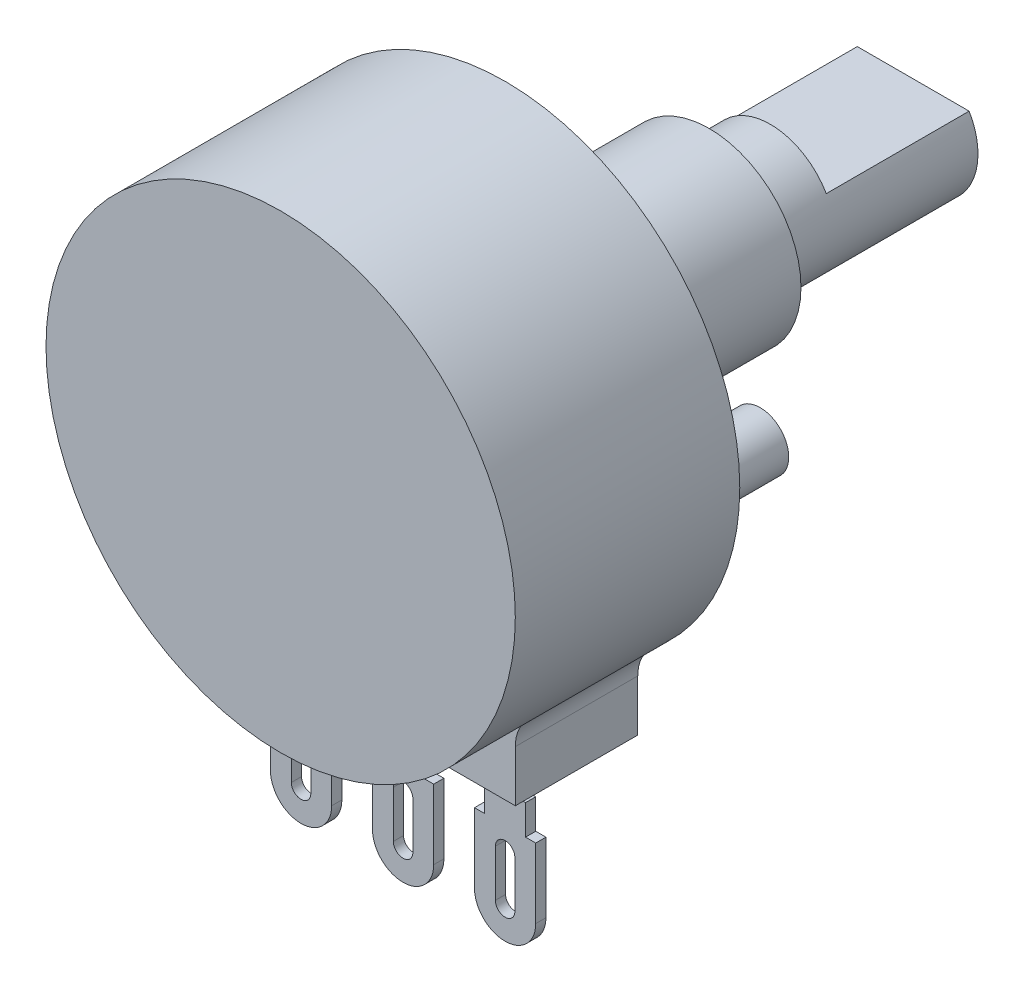
SolidWorks part; units mm, degrees
ref_plane "Front Plane" through (0, 0, 0) normal (0, 0, 1) x (1, 0, 0)
ref_plane "Top Plane" through (0, 0, 0) normal (0, 1, 0) x (1, 0, 0)
ref_plane "Right Plane" through (0, 0, 0) normal (1, 0, 0) x (0, 0, -1)
sketch "Sketch1" plane through (0, 0, 0) normal (1, 0, 0) x (0, 0, -1)
  line L0 (-360.0551, 0) -> (17642.7019, 0) construction
  line L1 (0, -360.0551) -> (0, 17642.7019) construction
  line L2 (0, 0) -> (0, 11.5)
  line L3 (0, 11.5) -> (11, 11.5)
  line L4 (11, 11.5) -> (11, 4.5)
  line L5 (11, 4.5) -> (21, 4.5)
  line L6 (21, 4.5) -> (21, 3.175)
  line L7 (21, 3.175) -> (31, 3.175)
  line L8 (31, 3.175) -> (31, 0)
  line L9 (0, 0) -> (31, 0)
  dimension "D1" = 23
  dimension "D2" = 11
  dimension "D3" = 10
  dimension "D4" = 20
  dimension "D5" = 9
  dimension "D6" = 6.35
revolve "Revolve1" add sketch "Sketch1" angle 360 about L9
sketch "Sketch2" plane through (0, 0, -11) normal (0, 0, -1) x (-1, 0, 0)
  circle A0 centre (-10, 0) radius 1.4
  dimension "D1" = 2.8
  dimension "D2" = 10
extrude "Boss-Extrude1" add sketch "Sketch2" along normal blind 2.5
ref_plane "Plane1" through (0, 0, -5) normal (0, 0, -1) x (-1, 0, 0)
sketch "Sketch3" plane through (0, 0, -5) normal (0, 0, -1) x (-1, 0, 0)
  line L0 (-1000, 0) -> (49000, 0) construction
  line L5 (0, -1000) -> (0, 49000) construction
  line L7 (-6.5, -8.3134) -> (6.5, -8.3134)
  line L8 (-6.5, -8.3134) -> (-6.5, -13)
  line L9 (-6.5, -13) -> (6.5, -13)
  line L10 (6.5, -8.3134) -> (6.5, -13)
  line L11 (-6.5, -8.3134) -> (6.5, -13) construction
  line L12 (-6.5, -13) -> (6.5, -8.3134) construction
  point P1 (0, -10.6567)
  dimension "D1" = 13
  dimension "D2" = 13
extrude "Boss-Extrude3" add sketch "Sketch3" along normal up to surface (6 mm away) up to face at (11.4, 0, -11)
fillet "Fillet1" radius 2 2 edges at (-6.5, -9.4868, -8) (6.5, -9.4868, -8)
ref_plane "Plane2" through (0, 0, -6) normal (0, 0, -1) x (-1, 0, 0)
sketch "Sketch4" plane through (0, 0, -6) normal (0, 0, -1) x (-1, 0, 0)
  line L0 (-5.4205, -13) -> (-5.4205, -13.6163)
  line L1 (-1.5, -18.5) -> (-1.5, -15.0805)
  line L2 (6.5, -13) -> (-6.5, -13) construction
  line L3 (-5.4205, -13.6163) -> (-6, -13.6163)
  line L4 (-6, -13.6163) -> (-6, -15.0805)
  line L5 (-6, -15.0805) -> (-6.5, -15.0805)
  line L6 (-6.5, -15.0805) -> (-6.5, -18.5)
  line L7 (-3.5, -18.5) -> (-3.5, -15.0805)
  line L8 (-3.5, -15.0805) -> (-4, -15.0805)
  line L9 (-4, -15.0805) -> (-4, -13.6163)
  line L10 (-4, -13.6163) -> (-3.4205, -13.6163)
  line L11 (-3.4205, -13.6163) -> (-3.4205, -13)
  line L12 (-1004.7659, -20) -> (48995.2341, -20) construction
  line L13 (-1000, 0) -> (49000, 0) construction
  line L14 (0, -1000) -> (0, 49000) construction
  line L15 (3.4205, -13.6163) -> (3.4205, -13)
  line L16 (4, -13.6163) -> (3.4205, -13.6163)
  line L17 (4, -15.0805) -> (4, -13.6163)
  line L18 (3.5, -15.0805) -> (4, -15.0805)
  line L19 (3.5, -18.5) -> (3.5, -15.0805)
  line L20 (6.5, -15.0805) -> (6.5, -18.5)
  line L21 (6, -15.0805) -> (6.5, -15.0805)
  line L22 (6, -13.6163) -> (6, -15.0805)
  line L23 (5.4205, -13.6163) -> (6, -13.6163)
  line L24 (5.4205, -13) -> (5.4205, -13.6163)
  line L25 (-1.5, -15.0805) -> (-1, -15.0805)
  line L26 (-1, -15.0805) -> (-1, -13.6163)
  line L27 (-1, -13.6163) -> (-1.5, -13.6163)
  line L28 (-1.5, -13.6163) -> (-1.5, -13)
  line L29 (1.5, -18.5) -> (1.5, -15.0805)
  line L30 (1.5, -13.6163) -> (1.5, -13)
  line L31 (1, -13.6163) -> (1.5, -13.6163)
  line L32 (1, -15.0805) -> (1, -13.6163)
  line L33 (1.5, -15.0805) -> (1, -15.0805)
  line L34 (-5, -18.5) -> (-5, -16.2024) construction
  line L35 (-5.4772, -18.5) -> (-5.4772, -16.2024)
  line L36 (-4.5228, -18.5) -> (-4.5228, -16.2024)
  line L37 (0, -18.5) -> (0, -16.2024) construction
  line L38 (-0.4772, -18.5) -> (-0.4772, -16.2024)
  line L39 (0.4772, -18.5) -> (0.4772, -16.2024)
  line L40 (5, -18.5) -> (5, -16.2024) construction
  line L41 (4.5228, -18.5) -> (4.5228, -16.2024)
  line L42 (5.4772, -18.5) -> (5.4772, -16.2024)
  line L43 (-5.4205, -13) -> (-3.4205, -13)
  line L44 (-1.5, -13) -> (1.5, -13)
  line L45 (3.4205, -13) -> (5.4205, -13)
  arc A0 (-6.5, -18.5) -> (-3.5, -18.5) centre (-5, -18.5) ccw
  arc A1 (6.5, -18.5) -> (3.5, -18.5) centre (5, -18.5) cw
  arc A2 (-1.5, -18.5) -> (1.5, -18.5) centre (0, -18.5) ccw
  arc A3 (-5.4772, -18.5) -> (-4.5228, -18.5) centre (-5, -18.5) ccw
  arc A4 (-4.5228, -16.2024) -> (-5.4772, -16.2024) centre (-5, -16.2024) ccw
  arc A5 (-0.4772, -18.5) -> (0.4772, -18.5) centre (0, -18.5) ccw
  arc A6 (0.4772, -16.2024) -> (-0.4772, -16.2024) centre (0, -16.2024) ccw
  arc A7 (4.5228, -18.5) -> (5.4772, -18.5) centre (5, -18.5) ccw
  arc A8 (5.4772, -16.2024) -> (4.5228, -16.2024) centre (5, -16.2024) ccw
  point P19 (-5, -20)
  point P37 (-5, -17.3512)
  point P55 (0, -17.3512)
  point P61 (5, -17.3512)
  dimension "D2" = 20
  dimension "D1" = 3
  dimension "D3" = 13
  dimension "D4" = 2
  dimension "D5" = 2
  dimension "D6" = 2
  dimension "D7" = 3
extrude "Boss-Extrude4" add sketch "Sketch4" along normal blind 0.5
sketch "Sketch5" plane through (0, 0, -31) normal (0, 0, -1) x (-1, 0, 0)
  line L0 (-3.175, 0) -> (3.175, 0) construction
  line L1 (-2.7405, 1.6031) -> (2.7405, 1.6031)
  circle A0 centre (0, 0) radius 3.175 construction
  arc A1 (2.7405, 1.6031) -> (-2.7405, 1.6031) centre (0, 0) ccw
extrude "Cut-Extrude1" cut sketch "Sketch5" against normal blind 7
